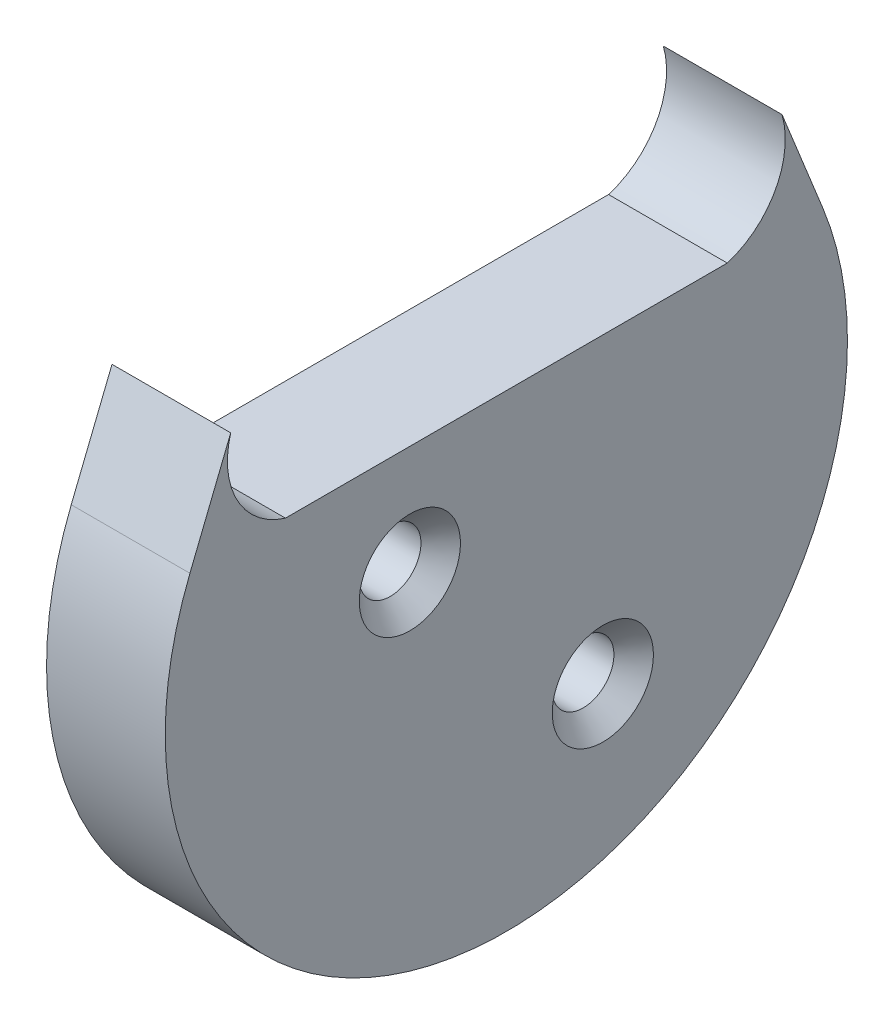
SolidWorks part; units mm, degrees
material "ABS"
ref_plane "Front" through (0, 0, 0) normal (0, 0, 1) x (1, 0, 0)
ref_plane "Top" through (0, 0, 0) normal (0, 1, 0) x (1, 0, 0)
ref_plane "Right" through (0, 0, 0) normal (1, 0, 0) x (0, 0, -1)
sketch "Sketch1" plane through (0, 0, 0) normal (1, 0, 0) x (0, 0, -1)
  line L0 (-11.5955, 4.6684) -> (11.5955, 4.6684)
  line L1 (-11.5955, 4.6684) -> (-10.1016, 8.379)
  line L2 (11.5955, 4.6684) -> (10.1016, 8.379)
  arc A0 (-11.5955, 4.6684) -> (11.5955, 4.6684) centre (0, 0) ccw
  arc A1 (-10.1016, 8.379) -> (-8.0955, 4.6684) centre (-7.2218, 7.5384) ccw
  arc A2 (10.1016, 8.379) -> (8.0955, 4.6684) centre (7.2218, 7.5384) cw
  dimension "D1" = 12.5
  dimension "D4" = 3.5
  dimension "3" = 3
  dimension "D2" = 23.191
  dimension "D3" = 4
  dimension "D5" = 3.5
extrude "Boss-Extrude1" add sketch "Sketch1" along normal mid plane 4.35 contours A1 L1 L0 | L2 A2 L0
sketch "Sketch2" plane through (2.175, 0, 0) normal (1, 0, 0) x (0, 0, -1)
  line L0 (0, 4.6684) -> (0, 0.6684) construction
  line L2 (-3.5355, 0.6684) -> (3.5355, 0.6684) construction
  line L3 (3.5355, 0.6684) -> (-3.5355, -6.4026) construction
  line L4 (-3.5355, 0.6684) -> (3.5355, -6.4026) construction
  line L5 (-8.0955, 4.6684) -> (8.0955, 4.6684) construction
  point P7 (0, 0.6684)
  point P10 (0, -2.8671)
  dimension "D1" = 4
  dimension "D2" = 10
hole_wizard "#2 Clearance Hole2" positions "3DSketch1" profile "Sketch6" hole size "#2" standard "ANSI Inch" end condition through all
sketch3d "3DSketch1"
  point P10 (2.175, 0.6684, 3.5355)
  point P13 (2.175, -6.4026, -3.5355)
sketch "Sketch6" plane through (2.175, 0.6684, 3.5355) normal (0, 1, 0) x (0, 0, -1)
  line L0 (0, 0) -> (0, 4.35)
  line L1 (0, 4.35) -> (1.1303, 4.35)
  line L2 (1.1303, 4.35) -> (1.1303, 0.7239)
  line L3 (1.1303, 0.7239) -> (1.8542, 0)
  line L5 (1.8542, 0) -> (0, 0)
  line L6 (-1.1303, 0.7239) -> (-1.8542, 0) construction
  line L11 (0, -6.35) -> (0, 107.95) construction
  dimension "Thru Hole Dia." = 2.2606
  dimension "Thru Hole Depth" = 4.35
  dimension "Near C'Sink Dia." = 3.7084
  dimension "Near C'Sink Angle" = 90
move or copy body "Body-Move/Copy1" [suppressed] bodies to move or copy 105
